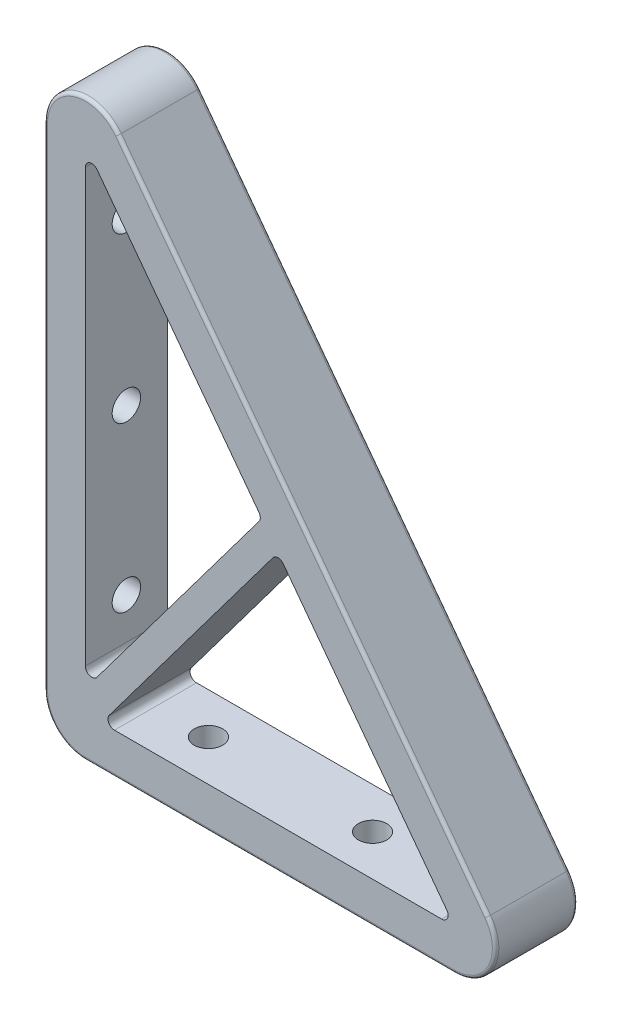
SolidWorks part; units mm, degrees
ref_plane "Front Plane" through (0, 0, 0) normal (0, 0, 1) x (1, 0, 0)
ref_plane "Top Plane" through (0, 0, 0) normal (0, 1, 0) x (1, 0, 0)
ref_plane "Right Plane" through (0, 0, 0) normal (1, 0, 0) x (0, 0, -1)
sketch "Sketch1" plane through (0, 0, 0) normal (0, 0, 1) x (1, 0, 0)
  line L0 (0, 0) -> (76.2, -101.6)
  line L1 (0, 0) -> (76.2, 0)
  line L2 (0, 0) -> (0, -101.6)
  line L3 (0, -101.6) -> (76.2, -101.6)
  line L4 (76.2, 0) -> (76.2, -101.6)
  line L5 (6.35, -19.05) -> (6.35, -95.25)
  line L6 (6.35, -95.25) -> (63.5, -95.25)
  line L7 (63.5, -95.25) -> (6.35, -19.05)
  line L8 (6.35, -95.25) -> (34.925, -57.15) construction
  line L9 (8.85, -95.25) -> (36.175, -58.8167)
  line L10 (6.35, -91.9167) -> (33.675, -55.4833)
  dimension "D1" = 101.6
  dimension "D2" = 76.2
  dimension "D3" = 6.35
  dimension "D4" = 6.35
  dimension "D5" = 6.35
  dimension "D6" = 4
  dimension "D7" = 2
extrude "Boss-Extrude1" add sketch "Sketch1" along normal blind 12.7 contours L2 L3 L0 L7 L6 L5 | L8 L6 L9 L7 | L5 L8 L7 L10
fillet "Fillet1" radius 6.35 3 edges at (0, 0, 6.35) (76.2, -101.6, 6.35) (0, -101.6, 6.35)
fillet "Fillet2" radius 1 6 edges at (63.5, -95.25, 6.35) (6.35, -19.05, 6.35) (36.175, -58.8167, 6.35) (33.675, -55.4833, 6.35) (6.35, -91.9167, 6.35) (8.85, -95.25, 6.35)
sketch "Sketch2" plane through (0, -101.6, 0) normal (0, -1, 0) x (1, 0, 0)
  line L0 (0, 0) -> (0, 12.7) construction
  line L1 (6.35, 12.7) -> (63.5, 12.7) construction
  circle A0 centre (19.05, 6.35) radius 2.2
  circle A1 centre (44.45, 6.35) radius 2.2
  dimension "D4" = 4.4
  dimension "D1" = 19.05
  dimension "D2" = 25.4
  dimension "D3" = 6.35
extrude "Cut-Extrude1" cut sketch "Sketch2" against normal up to next
sketch "Sketch3" plane through (0, 0, 0) normal (-1, 0, 0) x (0, 0, 1)
  line L0 (12.7, -19.05) -> (12.7, -95.25) construction
  line L1 (12.7, -101.6) -> (0, -101.6) construction
  circle A0 centre (6.35, -82.55) radius 2.2
  circle A1 centre (6.35, -57.15) radius 2.2
  circle A2 centre (6.35, -31.75) radius 2.2
  dimension "D1" = 4.4
  dimension "D2" = 6.35
  dimension "D3" = 19.05
  dimension "D4" = 25.4
  dimension "D5" = 25.4
extrude "Cut-Extrude2" cut sketch "Sketch3" against normal up to next
fillet "Fillet3" radius 0.5 12 edges at (4.342, -13.0259, 12.7) (4.342, -13.0259, 0) (40.005, -53.34, 0) (40.005, -53.34, 12.7) (69.1796, -98.0898, 12.7) (69.1796, -98.0898, 0) (34.925, -101.6, 12.7) (34.925, -101.6, 0) (1.8599, -99.7401, 12.7) (1.8599, -99.7401, 0) (0, -57.15, 0) (0, -57.15, 12.7)
